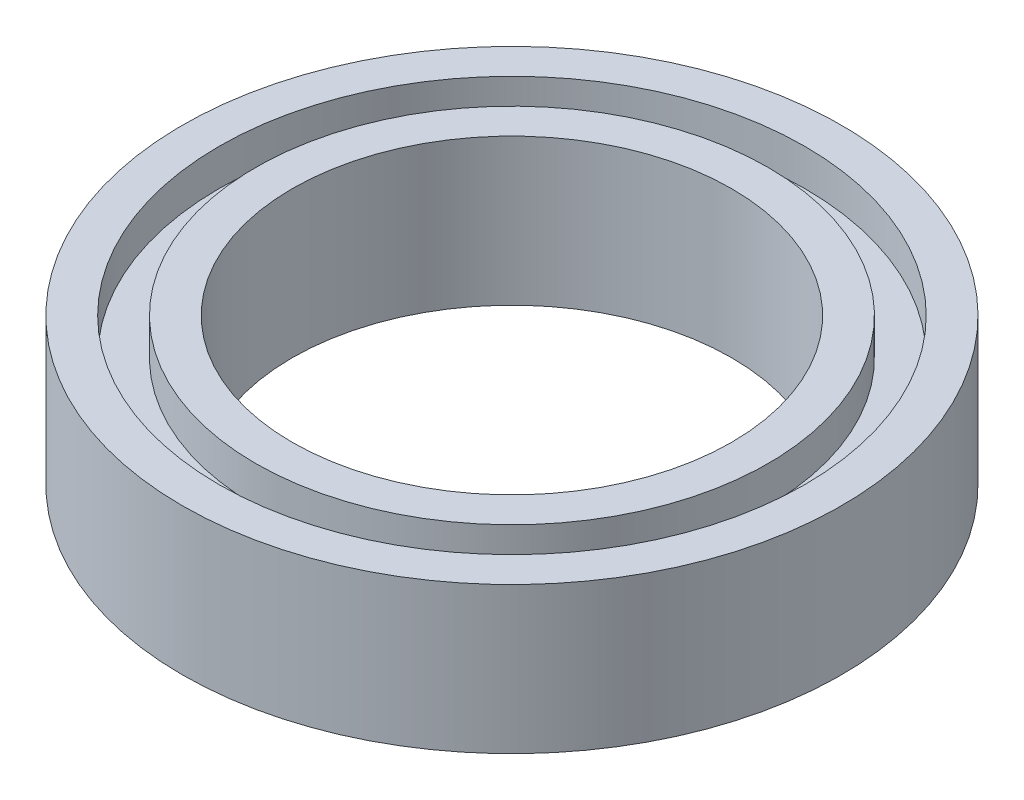
SolidWorks part; units mm, degrees
ref_plane "Front Plane" through (0, 0, 0) normal (0, 0, 1) x (1, 0, 0)
ref_plane "Top Plane" through (0, 0, 0) normal (0, 1, 0) x (1, 0, 0)
ref_plane "Right Plane" through (0, 0, 0) normal (1, 0, 0) x (0, 0, -1)
sketch "Sketch1" plane through (0, 0, 0) normal (0, 1, 0) x (1, 0, 0)
  circle A0 centre (0, 0) radius 9
  circle A1 centre (0, 0) radius 6
  dimension "D1" = 18
  dimension "D2" = 12
extrude "Boss-Extrude1" add sketch "Sketch1" along normal blind 4
sketch "Sketch2" plane through (0, 4, 0) normal (0, 1, 0) x (1, 0, 0)
  circle A0 centre (0, 0) radius 7
  circle A1 centre (0, 0) radius 8
  dimension "D1" = 16
  dimension "D2" = 14
extrude "Cut-Extrude1" cut sketch "Sketch2" against normal blind 1
sketch "Sketch3" plane through (0, 0, 0) normal (0, -1, 0) x (1, 0, 0)
  circle A0 centre (0, 0) radius 7
  circle A1 centre (0, 0) radius 8
  dimension "D1" = 16
  dimension "D2" = 14
extrude "Cut-Extrude2" cut sketch "Sketch3" against normal blind 1
